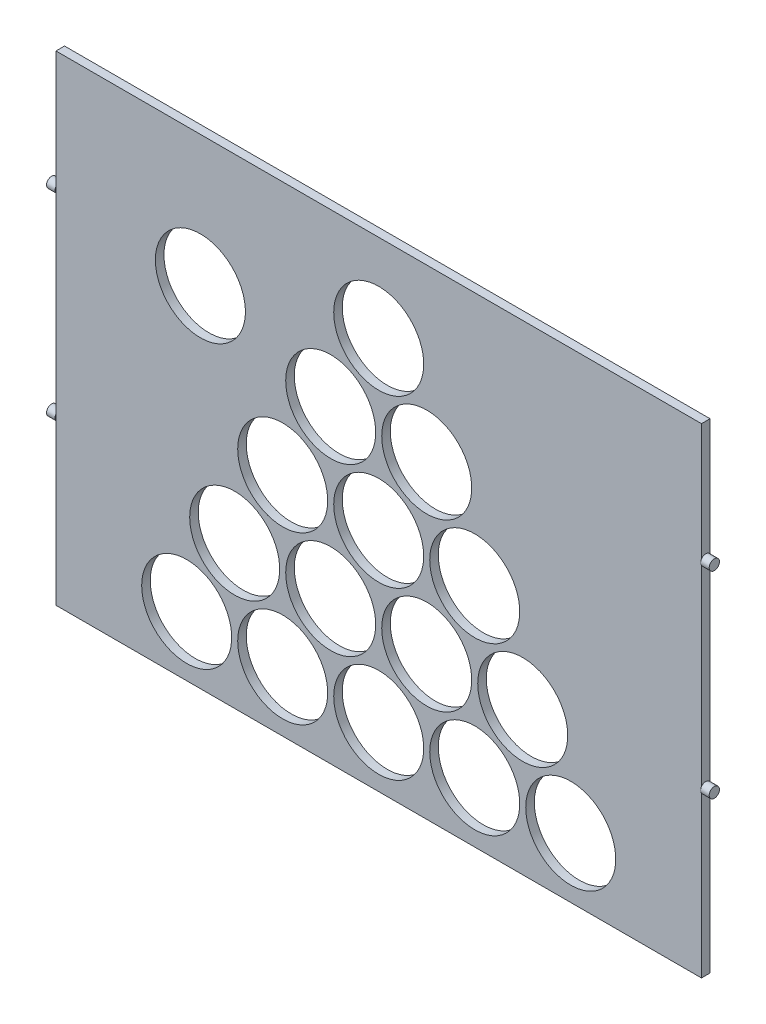
SolidWorks part; units mm, degrees
ref_plane "前视基准面" through (0, 0, 0) normal (0, 0, 1) x (1, 0, 0)
ref_plane "上视基准面" through (0, 0, 0) normal (0, 1, 0) x (1, 0, 0)
ref_plane "右视基准面" through (0, 0, 0) normal (1, 0, 0) x (0, 0, -1)
sketch "草图1" plane through (0, 0, 0) normal (0, 0, 1) x (1, 0, 0)
  line L1 (0, 0) -> (376.5, 0)
  line L2 (0, 0) -> (0, 280)
  line L3 (0, 280) -> (376.5, 280)
  line L4 (376.5, 0) -> (376.5, 280)
  point P5 (0, 0)
  point P6 (0, 0)
extrude "凸台-拉伸1" add sketch "草图1" along normal blind 5
sketch "草图2" plane through (0, 0, 5) normal (0, 0, 1) x (1, 0, 0)
  line L0 (0, -10.9252) -> (50, -10.9252) construction
  line L3 (163.25, 0) -> (163.25, -31.3199) construction
  line L5 (146.25, 35) -> (214.9239, 153.9468) construction
  line L6 (0, 35) -> (0, 0) construction
  line L7 (5, 35) -> (75, 35) construction
  circle A16 centre (84.25, 203.4974) radius 26.25
  circle A17 centre (188.25, 228.9897) radius 26.25
  circle A18 centre (160.25, 180.4923) radius 26.25
  circle A19 centre (216.25, 180.4923) radius 26.25
  circle A20 centre (244.25, 131.9948) radius 26.25
  circle A21 centre (132.25, 131.9948) radius 26.25
  circle A22 centre (188.25, 131.9948) radius 26.25
  circle A23 centre (272.25, 83.4974) radius 26.25
  circle A24 centre (216.25, 83.4974) radius 26.25
  circle A25 centre (104.25, 83.4974) radius 26.25
  circle A26 centre (160.25, 83.4974) radius 26.25
  circle A27 centre (300.25, 35) radius 26.25
  circle A28 centre (244.25, 35) radius 26.25
  circle A29 centre (188.25, 35) radius 26.25
  circle A30 centre (132.25, 35) radius 26.25
  circle A31 centre (76.25, 35) radius 26.25
extrude "切除-拉伸1" cut sketch "草图2" against normal blind 5
sketch "草图3" plane through (0, 0, 0) normal (-1, 0, 0) x (0, 0, 1)
  line L0 (2.5, 280) -> (2.5, 210) construction
  line L1 (5, 280) -> (0, 280) construction
  line L2 (2.5, 210) -> (2.5, 95) construction
  circle A0 centre (2.5, 210) radius 3
  circle A1 centre (2.5, 95) radius 3
extrude "凸台-拉伸2" add sketch "草图3" along normal blind 5
sketch "草图4" plane through (376.5, 0, 0) normal (1, 0, 0) x (0, 0, -1)
  line L0 (-2.5, 280) -> (-2.5, 210) construction
  line L1 (-5, 280) -> (0, 280) construction
  line L2 (-2.5, 210) -> (-2.5, 95) construction
  circle A0 centre (-2.5, 210) radius 3
  circle A1 centre (-2.5, 95) radius 3
extrude "凸台-拉伸3" add sketch "草图4" along normal blind 5
